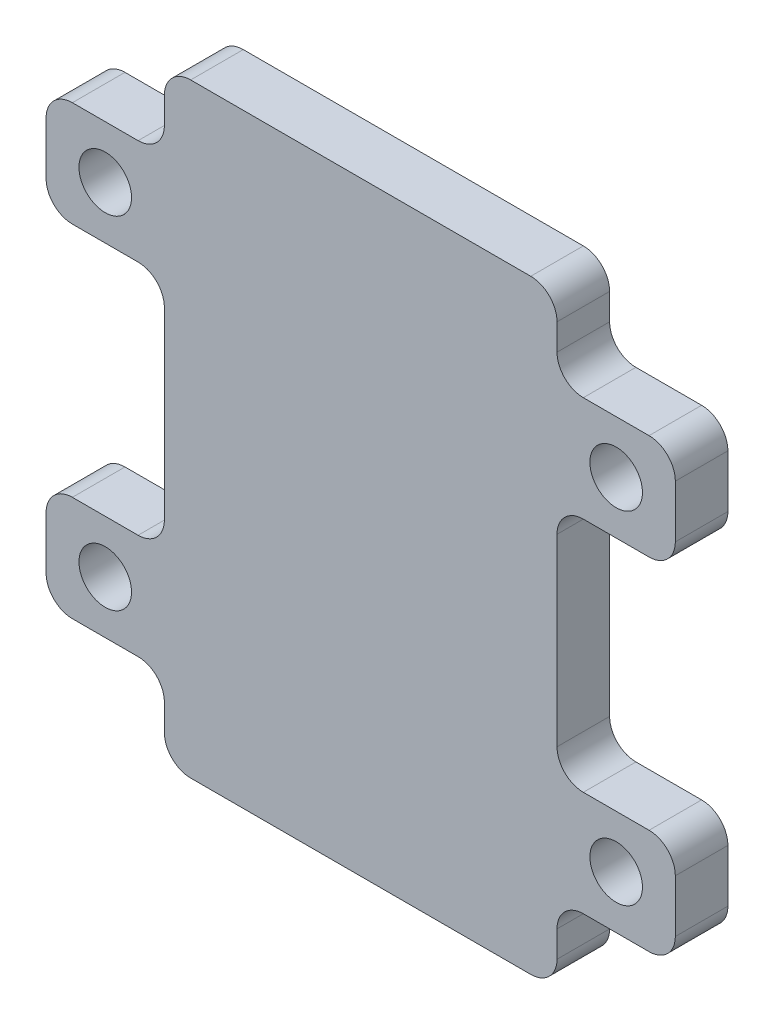
SolidWorks part; units mm, degrees
ref_plane "Front Plane" through (0, 0, 0) normal (0, 0, 1) x (1, 0, 0)
ref_plane "Top Plane" through (0, 0, 0) normal (0, 1, 0) x (1, 0, 0)
ref_plane "Right Plane" through (0, 0, 0) normal (1, 0, 0) x (0, 0, -1)
sketch "Sketch1" plane through (0, 0, 0) normal (0, 0, 1) x (1, 0, 0)
  line L0 (-3.734, 11) -> (-3.734, 10.5)
  line L1 (-4.234, 10) -> (-5.484, 10)
  line L2 (-5.984, 9.5) -> (-5.984, 8.5)
  line L3 (-5.484, 8) -> (-4.234, 8)
  line L4 (-3.734, 7.5) -> (-3.734, 4)
  line L5 (-4.234, 3.5) -> (-5.484, 3.5)
  line L6 (-5.984, 3) -> (-5.984, 2)
  line L7 (-5.484, 1.5) -> (-4.234, 1.5)
  line L8 (-3.734, 1) -> (-3.734, 0.5)
  line L12 (-4.859, 10) -> (-4.859, 8) construction
  line L13 (0, -6.5439) -> (0, 23.2179) construction
  line L14 (-3.234, 0) -> (3.234, 0)
  line L15 (-3.234, 11.5) -> (3.234, 11.5)
  line L29 (-4.859, 3.5) -> (-4.859, 1.5) construction
  line L30 (4.859, 3.5) -> (4.859, 1.5) construction
  line L31 (4.859, 10) -> (4.859, 8) construction
  line L32 (3.734, 1) -> (3.734, 0.5)
  line L33 (5.484, 1.5) -> (4.234, 1.5)
  line L34 (5.984, 3) -> (5.984, 2)
  line L35 (4.234, 3.5) -> (5.484, 3.5)
  line L36 (3.734, 7.5) -> (3.734, 4)
  line L37 (5.484, 8) -> (4.234, 8)
  line L38 (5.984, 9.5) -> (5.984, 8.5)
  line L39 (4.234, 10) -> (5.484, 10)
  line L40 (3.734, 11) -> (3.734, 10.5)
  arc A0 (-3.734, 10.5) -> (-4.234, 10) centre (-4.234, 10.5) cw
  arc A1 (-5.484, 10) -> (-5.984, 9.5) centre (-5.484, 9.5) ccw
  arc A2 (-5.984, 8.5) -> (-5.484, 8) centre (-5.484, 8.5) ccw
  arc A3 (-4.234, 8) -> (-3.734, 7.5) centre (-4.234, 7.5) cw
  arc A4 (-3.734, 4) -> (-4.234, 3.5) centre (-4.234, 4) cw
  arc A5 (-5.484, 3.5) -> (-5.984, 3) centre (-5.484, 3) ccw
  arc A6 (-5.984, 2) -> (-5.484, 1.5) centre (-5.484, 2) ccw
  arc A7 (-4.234, 1.5) -> (-3.734, 1) centre (-4.234, 1) cw
  arc A8 (-3.734, 0.5) -> (-3.234, 0) centre (-3.234, 0.5) ccw
  arc A9 (-3.234, 11.5) -> (-3.734, 11) centre (-3.234, 11) ccw
  circle A20 centre (-4.859, 9) radius 0.5
  circle A21 centre (-4.859, 2.5) radius 0.5
  circle A22 centre (4.859, 2.5) radius 0.5
  circle A23 centre (4.859, 9) radius 0.5
  arc A24 (3.234, 11.5) -> (3.734, 11) centre (3.234, 11) cw
  arc A25 (3.734, 0.5) -> (3.234, 0) centre (3.234, 0.5) cw
  arc A26 (4.234, 1.5) -> (3.734, 1) centre (4.234, 1) ccw
  arc A27 (5.984, 2) -> (5.484, 1.5) centre (5.484, 2) cw
  arc A28 (5.484, 3.5) -> (5.984, 3) centre (5.484, 3) cw
  arc A29 (3.734, 4) -> (4.234, 3.5) centre (4.234, 4) ccw
  arc A30 (4.234, 8) -> (3.734, 7.5) centre (4.234, 7.5) ccw
  arc A31 (5.984, 8.5) -> (5.484, 8) centre (5.484, 8.5) cw
  arc A32 (5.484, 10) -> (5.984, 9.5) centre (5.484, 9.5) cw
  arc A33 (3.734, 10.5) -> (4.234, 10) centre (4.234, 10.5) ccw
  point P30 (-11.5883, 25.9842)
  point P33 (-4.859, 2.8765)
  point P36 (0, 0)
  point P37 (-4.9804, 12.1955)
  point P45 (-7.7404, 29.0796)
  point P46 (-6.0147, 21.6273)
  point P47 (-4.859, 3.2745)
  point P48 (0, 24.6797)
  point P49 (-7.0941, 20.1841)
  point P50 (-4.859, 8.5396)
  point P51 (-5.9817, 9.0829)
  point P52 (-5.984, 16.4674)
  point P53 (-4.859, 14.0198)
  point P54 (-3.734, 11.5)
  point P55 (-5.484, 4.3106)
  point P56 (0, 16.1063)
  point P96 (0, 11.5)
  dimension "D1" = 0.5
  dimension "D3" = 1
  dimension "D2" = 6.5
  dimension "D4" = 9.718
  dimension "D5" = 2.25
  dimension "D6" = 2.5
  dimension "D7" = 2
extrude "Boss-Extrude1" add sketch "Sketch1" along normal blind 1
